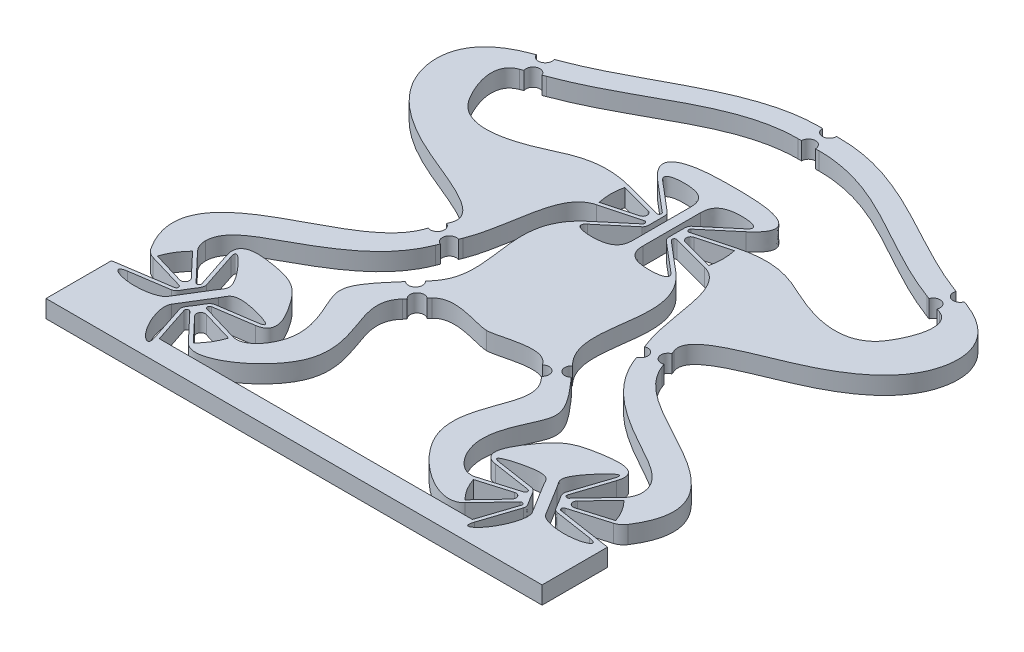
SolidWorks part; units mm, degrees
ref_plane "Front Plane" through (0, 0, 0) normal (0, 0, 1) x (1, 0, 0)
ref_plane "Top Plane" through (0, 0, 0) normal (0, 1, 0) x (1, 0, 0)
ref_plane "Right Plane" through (0, 0, 0) normal (1, 0, 0) x (0, 0, -1)
sketch "Basic" plane through (0, 0, 0) normal (0, 1, 0) x (1, 0, 0)
  line L0 (-100, 0) -> (-40, 67.082) construction
  line L1 (-40, 67.082) -> (0, 169.5515) construction
  line L2 (0, 169.5515) -> (-60, 102.4695) construction
  line L3 (-60, 102.4695) -> (-100, 0) construction
  line L4 (-40, 67.082) -> (40, 67.082) construction
  line L5 (-60, 102.4695) -> (-115.9233, 212.8627) construction
  line L6 (-115.9233, 212.8627) -> (0, 169.5515) construction
  line L7 (-115.9233, 212.8627) -> (0, 256.1738) construction
  line L8 (0, 256.1738) -> (0, 169.5515) construction
  line L9 (115.9233, 212.8627) -> (0, 256.1738) construction
  line L10 (115.9233, 212.8627) -> (0, 169.5515) construction
  line L11 (60, 102.4695) -> (115.9233, 212.8627) construction
  line L12 (60, 102.4695) -> (100, 0) construction
  line L13 (0, 169.5515) -> (60, 102.4695) construction
  line L14 (40, 67.082) -> (0, 169.5515) construction
  line L15 (100, 0) -> (40, 67.082) construction
  point P0 (-100, 0)
  point P1 (-40, 67.082)
  point P2 (0, 169.5515)
  point P14 (0, 67.082)
  dimension "l1/2" = 100
  dimension "l2" = 90
  dimension "l3/2" = 40
  dimension "couplerLength" = 110
  dimension "couplerAngle" = 68.676
  dimension "couplerAngle2" = 68.676
  dimension "D1" = 68.676
  dimension "OAngle" = 69.513
  dimension "D3" = 69.513
sketch "Sketch4" plane through (0, 0, 0) normal (0, 1, 0) x (1, 0, 0)
  line L0 (-50.1021, 76.1176) -> (-24.4518, 53.1753) construction
  line L1 (0, 256.1738) -> (0, 169.5515) construction
  line L2 (-31.4082, 76.6879) -> (-47.0503, 59.1995) construction
  line L4 (-47.1388, 68.1006) -> (-48.4721, 66.6099)
  line L5 (-38.1945, 60.1006) -> (-39.5279, 58.6099)
  line L6 (-32.8612, 66.0635) -> (-31.5279, 67.5542)
  line L7 (-41.8055, 74.0635) -> (-40.4721, 75.5542)
  line L8 (-2.8, 185.99) -> (-2.8, 150.4776)
  line L10 (-5.8, 171.0064) -> (-5.8, 174.2297) construction
  line L14 (-7.9995, 207.9242) -> (7.9995, 207.9242) construction
  line L15 (0, 207.9242) -> (0, 67.082)
  line L18 (-100, 0) -> (-40, 67.082) construction
  line L19 (-115.9233, 212.8627) -> (0, 256.1738) construction
  line L20 (-55.8653, 96.5615) -> (-56.5926, 94.6984)
  line L21 (-64.1347, 108.3775) -> (-63.4074, 110.2406)
  line L22 (-72.6255, 107.398) -> (-40.483, 94.8509) construction
  line L23 (-52.9562, 104.0139) -> (-52.2289, 105.8769)
  line L24 (-55.61, 113.7156) -> (-64.28, 91.5052) construction
  line L25 (-67.0438, 100.9252) -> (-67.7711, 99.0621)
  line L26 (-121.6167, 228.1012) -> (-109.5404, 195.7788) construction
  line L27 (-121.7702, 217.0832) -> (-123.6438, 216.3832)
  line L28 (-110.0763, 208.6421) -> (-108.2028, 209.3421)
  line L29 (-103.9501, 217.3361) -> (-126.2848, 208.9914) construction
  line L30 (-117.5704, 205.8422) -> (-119.4439, 205.1422)
  line L31 (-114.2762, 219.8831) -> (-112.4027, 220.5831)
  line L32 (-60, 102.4695) -> (-100, 0) construction
  line L38 (12.8937, 256.1738) -> (-10.9489, 256.1738) construction
  line L39 (0, 265.543) -> (0, 231.0383) construction
  line L40 (4, 250.1738) -> (6, 250.1738) construction
  line L41 (4, 262.1738) -> (6, 262.1738) construction
  line L42 (-4, 250.1738) -> (-6, 250.1738)
  line L43 (-4, 262.1738) -> (-6, 262.1738)
  line L55 (0, -30.075) -> (-89.0686, -30.075)
  line L56 (-141.1166, -5.2594) -> (-141.1166, -42.4879)
  line L57 (-40, 67.082) -> (40, 67.082) construction
  line L58 (-141.1166, -42.4879) -> (0, -42.4879)
  line L60 (0, -30.075) -> (0, -42.4879)
  line L62 (0, 258.1738) -> (0, 254.1738)
  line L63 (-82.2118, 28.9516) -> (-117.7882, -28.9516) construction
  line L64 (-112.3171, 4.7336) -> (-130.3636, 10.1021)
  line L65 (-109.8172, 1.9033) -> (-130.9354, 8.1856)
  line L66 (-100, 0) -> (-123.139, 14.2168) construction
  line L67 (-130.9354, 8.1856) -> (-109.8172, 1.9033)
  line L68 (-109.0313, 30.6991) -> (-102.1381, 9.7688)
  line L69 (-110.9314, 30.075) -> (-104.0393, 9.1479)
  line L70 (-121.2819, 23.8973) -> (-106.1343, 7.8975)
  line L71 (-106.1343, 7.8975) -> (-121.2819, 23.8973)
  line L72 (-109.7888, 8.8485) -> (-122.7332, 22.5211)
  line L73 (-131.7688, -3.8395) -> (-109.9859, -0.5307)
  line L74 (-131.4669, -5.8166) -> (-109.6806, -2.5072)
  line L80 (-131.7688, -3.8395) -> (-141.1166, -5.2594)
  line L81 (-94.7503, -2.5351) -> (-92.7099, 0.7859) construction
  line L82 (-97.1835, 9.9327) -> (-107.4112, -6.7137)
  line L83 (-92.4121, 7.0011) -> (-102.6399, -9.6453)
  line L84 (0, 198.1371) -> (0, 140.966) construction
  line L85 (-12.9725, 167.1367) -> (-31.1591, 162.2637)
  line L86 (-9.3609, 166.0339) -> (-30.6429, 160.3314)
  line L87 (-90.9687, -30.6991) -> (-97.8619, -9.7688)
  line L88 (-89.0686, -30.075) -> (-95.9607, -9.1479)
  line L89 (-87.6829, -4.7336) -> (-69.6364, -10.1021)
  line L90 (-90.1828, -1.9033) -> (-69.0646, -8.1856)
  line L91 (-69.0646, -8.1856) -> (-90.1828, -1.9033)
  line L92 (-68.2312, 3.8395) -> (-90.0141, 0.5307)
  line L93 (-68.5331, 5.8166) -> (-90.3194, 2.5072)
  line L94 (-78.7181, -23.8973) -> (-93.8657, -7.8975)
  line L95 (-93.8657, -7.8975) -> (-78.7181, -23.8973)
  line L96 (-90.2112, -8.8485) -> (-77.2668, -22.5211)
  line L97 (0, 169.5515) -> (-41.2523, 169.5515) construction
  line L98 (-30.6429, 160.3314) -> (-9.3609, 166.0339)
  line L99 (-23.7658, 190.9802) -> (-6.9356, 176.7555)
  line L100 (-25.058, 189.4537) -> (-8.2305, 175.2313)
  line L101 (-30.6429, 178.7717) -> (-9.3609, 173.0692)
  line L102 (-9.3609, 173.0692) -> (-30.6429, 178.7717)
  line L103 (-12.9725, 171.9664) -> (-31.1591, 176.8394)
  line L104 (-25.058, 149.6493) -> (-8.2305, 163.8718)
  line L105 (-23.7658, 148.1229) -> (-6.9356, 162.3476)
  arc A0 (-47.1388, 68.1006) -> (-41.8055, 74.0635) centre (-44.4721, 71.082) ccw
  arc A1 (-38.1945, 60.1006) -> (-32.8612, 66.0635) centre (-35.5279, 63.082) cw
  arc A6 (-55.8653, 96.5615) -> (-52.9562, 104.0139) centre (-54.4108, 100.2877) cw
  arc A7 (-67.0438, 100.9252) -> (-64.1347, 108.3775) centre (-65.5892, 104.6513) ccw
  arc A8 (-121.7702, 217.0832) -> (-114.2762, 219.8831) centre (-118.0232, 218.4832) ccw
  arc A9 (-117.5704, 205.8422) -> (-110.0763, 208.6421) centre (-113.8234, 207.2421) cw
  arc A12 (-4, 250.1738) -> (0, 254.1738) centre (0, 250.1738) cw
  arc A13 (-4, 262.1738) -> (0, 258.1738) centre (0, 262.1738) ccw
  arc A20 (-109.9859, -0.5307) -> (-109.8172, 1.9033) centre (-110.1736, 0.7051) ccw
  arc A22 (-112.3171, 4.7336) -> (-109.7888, 8.8485) centre (-111.6042, 7.1298) ccw
  arc A23 (-122.7332, 22.5211) -> (-130.3636, 10.1021) centre (-100, 0) ccw
  arc A24 (-121.2819, 23.8973) -> (-124.2041, 31.234) centre (-113.5325, 31.234) cw
  arc A25 (-130.9354, 8.1856) -> (-135.7763, 11.7962) centre (-128.436, 16.5872) cw
  arc A28 (-105.9147, -8.0633) -> (-107.4112, -6.7137) centre (-100, 0) cw construction
  arc A29 (-104.0393, 9.1479) -> (-106.1343, 7.8975) centre (-105.2266, 8.7569) cw
  arc A33 (-8.2305, 163.8718) -> (-9.3609, 166.0339) centre (-9.0374, 164.8265) ccw
  arc A34 (-12.9725, 167.1367) -> (-12.9725, 171.9664) centre (-13.6196, 169.5515) ccw
  arc A35 (-31.1591, 176.8394) -> (-31.1591, 162.2637) centre (0, 169.5515) ccw
  arc A36 (-104.5201, -8.9201) -> (-102.6399, -9.6453) centre (-100, 0) ccw construction
  arc A37 (-90.0141, 0.5307) -> (-90.1828, -1.9033) centre (-89.8264, -0.7051) ccw
  arc A40 (-69.6364, -10.1021) -> (-77.2668, -22.5211) centre (-100, 0) cw
  arc A41 (-90.2112, -8.8485) -> (-87.6829, -4.7336) centre (-88.3958, -7.1298) cw
  arc A42 (-5.9147, 161.4883) -> (-7.8139, 163.3111) centre (0, 169.5515) cw construction
  arc A43 (-95.9607, -9.1479) -> (-93.8657, -7.8975) centre (-94.7734, -8.7569) cw
  arc A44 (-8.2305, 175.2313) -> (-9.3609, 173.0692) centre (-9.0374, 174.2766) cw
  spline S0 degree 3 poles (-108.2028, 209.3421) (-69.2396, 223.8995) (-42.6858, 250.1738) (-6, 250.1738) knots 0 0 0 0 1 1 1 1
  spline S1 degree 3 poles (-112.4027, 220.5831) (-76.7304, 233.911) (-44.0894, 262.1738) (-6, 262.1738) knots 0 0 0 0 1 1 1 1
  spline S2 degree 3 poles (-30.6429, 160.3314) (-47.7586, 155.7453) (-43.9497, 127.0863) (-52.2289, 105.8769) knots 0 0 0 0 1 1 1 1
  spline S3 degree 3 poles (-119.4439, 205.1422) (-130.8577, 200.8778) (-121.6875, 178.5173) (-107.9445, 163.2981) (-83.1401, 165.5359) (-51.0938, 184.2515) (-30.6429, 178.7717) knots 0 0 0 0 0.228027 0.303299 0.752716 1 1 1 1
  spline S4 degree 3 poles (-123.6438, 216.3832) (-146.4506, 207.8622) (-155.1315, 174.1257) (-116.9868, 138.2272) (-58.4296, 122.9925) (-63.4074, 110.2406) knots 0 0 0 0 0.283699 0.638824 1 1 1 1
  spline S7 degree 3 poles (-110.9314, 30.075) (-114.6707, 41.4289) (-83.2763, 38.259) (-72.6737, 32.4939) (-57.4813, 5.4724) (-68.2312, 3.8395) knots 0 0 0 0 0.279768 0.720232 1 1 1 1
  spline S8 degree 3 poles (-109.0313, 30.6991) (-111.4681, 38.0982) (-89.9648, 15.4417) (-95.0413, 13.4193) (-97.1835, 9.9327) knots 0 0 0 0 0.378705 1 1 1 1
  spline S9 degree 3 poles (-23.7658, 190.9802) (-28.8424, 195.271) (-7.7444, 197.788) (-2.8, 191.7012) (-2.8, 185.99) knots 0 0 0 0 0.455542 1 1 1 1
  spline S10 degree 3 poles (-31.5279, 67.5542) (-24.5424, 75.3642) (-6.5513, 67.082) (0, 67.082) knots 0 0 0 0 1 1 1 1
  spline S11 degree 3 poles (-25.058, 189.4537) (-48.6202, 209.3684) (-5.0767, 207.9242) (0, 207.9242) knots 0 0 0 0 1 1 1 1
  spline S12 degree 3 poles (-68.5331, 5.8166) (-60.8314, 6.9865) (-90.76, 15.9302) (-90.2699, 10.4878) (-92.4121, 7.0011) knots 0 0 0 0 0.378705 1 1 1 1
  spline S13 degree 3 poles (-131.4669, -5.8166) (-137.431, -6.7225) (-130.0737, -12.8246) (-109.9611, -10.8638) (-107.4112, -6.7137) knots 0 0 0 0 0.364886 1 1 1 1
  spline S14 degree 3 poles (-102.1381, 9.7688) (-101.8586, 8.9201) (-102.4032, 7.0148) (-105.1788, 2.9906) (-106.1501, 1.0767) (-108.1292, -2.2716) (-109.6806, -2.5072) knots 0 0 0 0 0.184332 0.256485 0.721528 1 1 1 1
  spline S15 degree 3 poles (-90.9687, -30.6991) (-89.0817, -36.4289) (-97.8499, -32.6232) (-105.1898, -13.7954) (-102.6399, -9.6453) knots 0 0 0 0 0.364886 1 1 1 1
  spline S16 degree 3 poles (-90.3194, 2.5072) (-91.2027, 2.3731) (-92.6563, 1.0262) (-94.9919, -3.2683) (-96.2602, -4.9998) (-98.3528, -8.2784) (-97.8619, -9.7688) knots 0 0 0 0 0.184332 0.256485 0.721528 1 1 1 1
  spline S17 degree 3 poles (-48.4721, 66.6099) (-62.3716, 51.0698) (-63.5925, 41.0648) (-44.6287, 10.8133) (-61.9125, -10.3133) (-69.0646, -8.1856) knots 0 0 0 0 0.35343 0.749579 1 1 1 1
  spline S18 degree 3 poles (-78.7181, -23.8973) (-70.0177, -33.087) (-29.2243, -4.8133) (-37.3575, 29.2887) (-46.7483, 50.5372) (-39.5279, 58.6099) knots 0 0 0 0 0.440379 0.74639 1 1 1 1
  spline S19 degree 3 poles (-124.2041, 31.234) (-124.2041, 41.5227) (-89.896, 59.0688) (-64.0709, 75.5409) (-56.5926, 94.6984) knots 0 0 0 0 0.335502 1 1 1 1
  spline S20 degree 3 poles (-135.7763, 11.7962) (-154.286, 40.1552) (-110.2335, 67.576) (-73.4384, 84.5438) (-67.7711, 99.0621) knots 0 0 0 0 0.537438 1 1 1 1
  spline S21 degree 3 poles (-6.9356, 176.7555) (-6.0715, 176.0252) (-5.767, 174.3848) (-5.8534, 170.3771) (-5.7702, 167.051) (-5.8194, 163.291) (-6.9356, 162.3476) knots 0 0 0 0 0.23343 0.307494 0.740633 1 1 1 1
  spline S22 degree 3 poles (-25.058, 149.6493) (-51.0582, 127.6742) (-22.3992, 95.7604) (-40.4721, 75.5542) knots 0 0 0 0 1 1 1 1
  spline S23 degree 3 poles (-23.7658, 148.1229) (-28.8424, 143.8321) (-7.7444, 141.3151) (-2.8, 147.4019) (-2.8, 153.1131) knots 0 0 0 0 0.455542 1 1 1 1
  point P42 (0, 207.9242)
  point P240 (-15.3507, 155.2352)
  dimension "D1" = 4
  dimension "D3" = 8
  dimension "D6" = 2.8
  dimension "D16" = 4
  dimension "D21" = 4
  dimension "D31" = 4
  dimension "D37" = 2.8
  dimension "D38" = 32
  dimension "D41" = 1.25
  dimension "D44" = 10
  dimension "D45" = 2.5
  dimension "D47" = 2
  dimension "D50" = 10
  dimension "D51" = 2.5
  dimension "D52" = 32
  dimension "D53" = 90
  dimension "D48" = 1.25
  dimension "D2" = 6
  dimension "D4" = 2
  dimension "D5" = 2
  dimension "D17" = 6
  dimension "D18" = 8
  dimension "D19" = 2
  dimension "D22" = 6
  dimension "D23" = 8
  dimension "D24" = 2
  dimension "D25" = 2
  dimension "D32" = 6
  dimension "D33" = 8
  dimension "D34" = 2
  dimension "D35" = 2
  dimension "D40" = 2
  dimension "D42" = 10.198
  dimension "D43" = 15
  dimension "D46" = 2
  dimension "D49" = 10.198
  dimension "D54" = 3.55
  dimension "D55" = 5.8
  dimension "D56" = 15
  dimension "D57" = 90
  dimension "D58" = 3.55
  dimension "D59" = 5.8
sketch "Sketch5" plane through (0, 0, 0) normal (0, 1, 0) x (1, 0, 0)
  line L0 (-14.0529, 35.7209) -> (3.5631, -35.7209) construction
  line L1 (-14.234, -4.3814) -> (-33.5107, -15.0015)
  line L2 (-13.1807, -6.0846) -> (-32.5182, -16.7382)
  line L3 (-5.2449, 0) -> (37.2446, 10.477) construction
  line L4 (-32.5182, -16.7382) -> (-13.1807, -6.0846)
  line L5 (-32.8384, 16.2049) -> (-13.6886, 5.3576)
  line L6 (-33.7969, 14.4493) -> (-14.5868, 3.5678)
  line L7 (-37.1732, 2.1404) -> (-15.0997, 1.6979)
  line L8 (-15.0997, 1.6979) -> (-37.1732, 2.1404)
  line L9 (-15.2404, -0.2997) -> (-37.2446, 0.1414)
  line L10 (-23.8067, -26.0665) -> (-11.8573, -7.5017)
  line L11 (-22.1418, -27.1752) -> (-10.23, -8.6688)
  arc A0 (-11.8573, -7.5017) -> (-13.1807, -6.0846) centre (-12.6982, -6.9605) ccw
  arc A1 (-14.234, -4.3814) -> (-13.1807, -6.0846) centre (-5.2449, 0) ccw
  arc A2 (-11.8573, -7.5017) -> (-10.23, -8.6688) centre (-5.2449, 0) ccw
  arc A3 (-33.5107, -15.0015) -> (-32.5182, -16.7382) centre (-5.2449, 0) ccw
  arc A4 (-23.8067, -26.0665) -> (-22.1418, -27.1752) centre (-5.2449, 0) ccw
  arc A5 (-33.7969, 14.4493) -> (-32.8384, 16.2049) centre (-5.2449, 0) cw
  arc A6 (-37.2446, 0.1414) -> (-37.1732, 2.1404) centre (-5.2449, 0) cw
  arc A7 (-14.5868, 3.5678) -> (-13.6886, 5.3576) centre (-5.2449, 0) cw
  arc A8 (-14.234, -4.3814) -> (-15.2404, -0.2997) centre (-5.2449, 0) cw
  arc A9 (-14.5868, 3.5678) -> (-15.0997, 1.6979) centre (-15.0797, 2.6977) cw
  point P8 (-16.1859, -17.922)
  dimension "D1" = 64
  dimension "D4" = 1
  dimension "D7" = 10
  dimension "D2" = 2
  dimension "D3" = 2
  dimension "D5" = 10.198
  dimension "D6" = 15
extrude "Boss-Extrude1" add sketch "Sketch4" along normal blind 10
mirror "Mirror1" about plane through (0, 10, 0) normal (1, 0, 0) of bodies 101
equation "\"couplerAngle\"= \"couplerAngle@Basic\""
equation "\"couplerAngle2@Basic\"=\"couplerAngle\""
equation "\"D1@Basic\"=\"couplerAngle\""
equation "\"OAngle\"= \"OAngle@Basic\""
equation "\"D3@Basic\"=\"OAngle\""
equation "\"beta\"= 0.25"
equation "\"t\"= 2mm"
equation "\"D\"= \"t\" / \"beta\""
